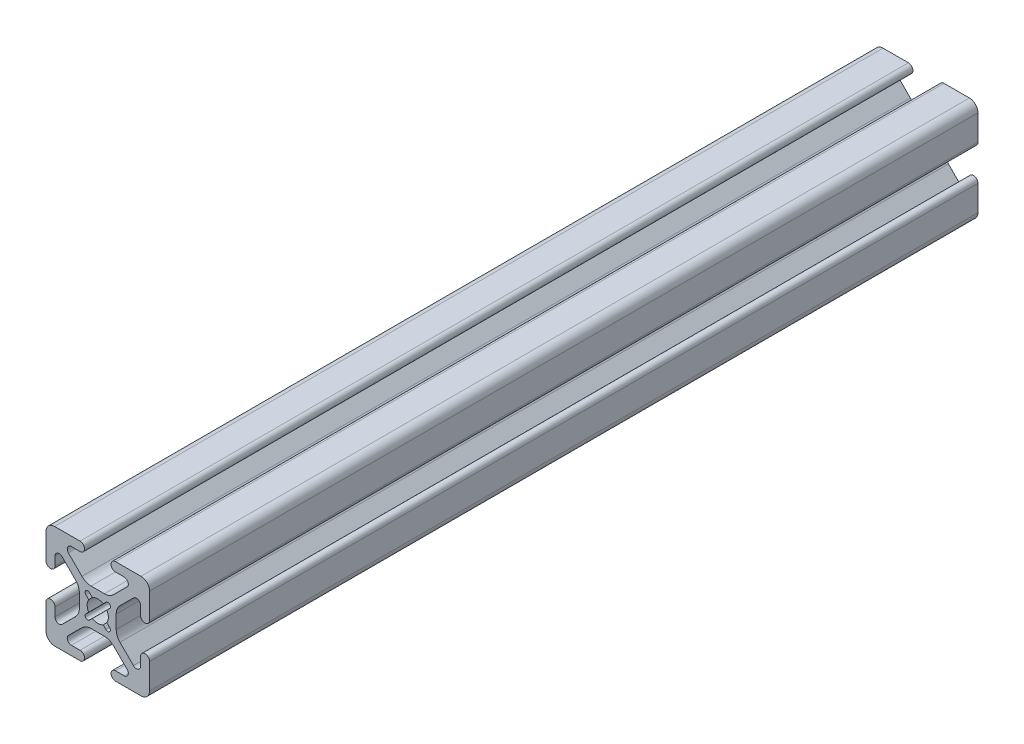
SolidWorks part; units mm, degrees
material "6105-T5 Aluminum"
ref_plane "Front Plane" through (0, 0, 0) normal (0, 0, 1) x (1, 0, 0)
ref_plane "Top Plane" through (0, 0, 0) normal (0, 1, 0) x (1, 0, 0)
ref_plane "Right Plane" through (0, 0, 0) normal (1, 0, 0) x (0, 0, -1)
sketch "Sketch1" plane through (0, 0, 0) normal (0, 0, 1) x (1, 0, 0)
  line L0 (-2.8605, -1.9692) -> (-2.2319, -1.3405)
  line L1 (-2.2319, 1.3405) -> (-2.8605, 1.9692)
  line L2 (-1.9692, 2.8605) -> (-1.3405, 2.2319)
  line L3 (1.3405, 2.2319) -> (1.9692, 2.8605)
  line L4 (2.8605, 1.9692) -> (2.2319, 1.3405)
  line L5 (2.2319, -1.3405) -> (2.8605, -1.9692)
  line L6 (1.9692, -2.8605) -> (1.3405, -2.2319)
  line L7 (-1.3405, -2.2319) -> (-1.9692, -2.8605)
  line L8 (-3.8846, 5.4471) -> (-7.1933, 8.7558)
  line L9 (1.6396, 4.5172) -> (-1.6396, 4.5172)
  line L10 (7.1933, 8.7558) -> (3.8846, 5.4471)
  line L11 (12.7, -10.5918) -> (12.7, -4.3561)
  line L12 (5.4471, 3.8846) -> (8.7558, 7.1933)
  line L13 (4.5172, -1.6396) -> (4.5172, 1.6396)
  line L14 (8.7558, -7.1933) -> (5.4471, -3.8846)
  line L15 (-10.5918, -12.7) -> (-4.3561, -12.7)
  line L16 (3.8846, -5.4471) -> (7.1933, -8.7558)
  line L17 (-1.6396, -4.5172) -> (1.6396, -4.5172)
  line L18 (-7.1933, -8.7558) -> (-3.8846, -5.4471)
  line L19 (-12.7, 10.5918) -> (-12.7, 4.3561)
  line L20 (-5.4471, -3.8846) -> (-8.7558, -7.1933)
  line L21 (-4.5172, 1.6396) -> (-4.5172, -1.6396)
  line L22 (-8.7558, 7.1933) -> (-5.4471, 3.8846)
  line L23 (-10.5918, 12.7) -> (-4.3561, 12.7)
  line L24 (-6.4749, 10.4902) -> (-4.3561, 10.4902)
  line L25 (-10.4902, 6.4749) -> (-10.4902, 4.3561)
  line L26 (-6.4749, -10.4902) -> (-4.3561, -10.4902)
  line L27 (10.4902, -6.4749) -> (10.4902, -4.3561)
  line L28 (4.3561, 12.7) -> (10.5918, 12.7)
  line L29 (4.3561, 10.4902) -> (6.4749, 10.4902)
  line L30 (-10.4902, -4.3561) -> (-10.4902, -6.4749)
  line L31 (-12.7, -4.3561) -> (-12.7, -10.5918)
  line L32 (4.3561, -10.4902) -> (6.4749, -10.4902)
  line L33 (4.3561, -12.7) -> (10.5918, -12.7)
  line L34 (12.7, 4.3561) -> (12.7, 10.5918)
  line L35 (10.4902, 4.3561) -> (10.4902, 6.4749)
  arc A0 (-2.8605, -1.9692) -> (-1.9692, -2.8605) centre (-2.4696, -2.4696) ccw
  arc A1 (-2.2319, 1.3405) -> (-2.2319, -1.3405) centre (0, 0) ccw
  arc A2 (-1.9692, 2.8605) -> (-2.8605, 1.9692) centre (-2.4696, 2.4696) ccw
  arc A3 (1.3405, 2.2319) -> (-1.3405, 2.2319) centre (0, 0) ccw
  arc A4 (2.8605, 1.9692) -> (1.9692, 2.8605) centre (2.4696, 2.4696) ccw
  arc A5 (2.2319, -1.3405) -> (2.2319, 1.3405) centre (0, 0) ccw
  arc A6 (1.9692, -2.8605) -> (2.8605, -1.9692) centre (2.4696, -2.4696) ccw
  arc A7 (-1.3405, -2.2319) -> (1.3405, -2.2319) centre (0, 0) ccw
  arc A8 (-3.8846, 5.4471) -> (-1.6396, 4.5172) centre (-1.6396, 7.6922) ccw
  arc A9 (1.6396, 4.5172) -> (3.8846, 5.4471) centre (1.6396, 7.6922) ccw
  arc A10 (5.4471, 3.8846) -> (4.5172, 1.6396) centre (7.6922, 1.6396) ccw
  arc A11 (4.5172, -1.6396) -> (5.4471, -3.8846) centre (7.6922, -1.6396) ccw
  arc A12 (3.8846, -5.4471) -> (1.6396, -4.5172) centre (1.6396, -7.6922) ccw
  arc A13 (-1.6396, -4.5172) -> (-3.8846, -5.4471) centre (-1.6396, -7.6922) ccw
  arc A14 (-5.4471, -3.8846) -> (-4.5172, -1.6396) centre (-7.6922, -1.6396) ccw
  arc A15 (-4.5172, 1.6396) -> (-5.4471, 3.8846) centre (-7.6922, 1.6396) ccw
  arc A16 (-12.7, -10.5918) -> (-10.5918, -12.7) centre (-10.5918, -10.5918) ccw
  arc A17 (10.5918, -12.7) -> (12.7, -10.5918) centre (10.5918, -10.5918) ccw
  arc A18 (12.7, 10.5918) -> (10.5918, 12.7) centre (10.5918, 10.5918) ccw
  arc A19 (-10.5918, 12.7) -> (-12.7, 10.5918) centre (-10.5918, 10.5918) ccw
  arc A20 (-8.7558, 7.1933) -> (-10.4902, 6.4749) centre (-9.4742, 6.4749) ccw
  arc A21 (-6.4749, 10.4902) -> (-7.1933, 8.7558) centre (-6.4749, 9.4742) ccw
  arc A22 (7.1933, 8.7558) -> (6.4749, 10.4902) centre (6.4749, 9.4742) ccw
  arc A23 (10.4902, 6.4749) -> (8.7558, 7.1933) centre (9.4742, 6.4749) ccw
  arc A24 (8.7558, -7.1933) -> (10.4902, -6.4749) centre (9.4742, -6.4749) ccw
  arc A25 (6.4749, -10.4902) -> (7.1933, -8.7558) centre (6.4749, -9.4742) ccw
  arc A26 (-7.1933, -8.7558) -> (-6.4749, -10.4902) centre (-6.4749, -9.4742) ccw
  arc A27 (-10.4902, -6.4749) -> (-8.7558, -7.1933) centre (-9.4742, -6.4749) ccw
  arc A28 (-4.3561, 10.4902) -> (-4.3561, 12.7) centre (-4.3561, 11.5951) ccw
  arc A29 (4.3561, 12.7) -> (4.3561, 10.4902) centre (4.3561, 11.5951) ccw
  arc A30 (-12.7, 4.3561) -> (-10.4902, 4.3561) centre (-11.5951, 4.3561) ccw
  arc A31 (-10.4902, -4.3561) -> (-12.7, -4.3561) centre (-11.5951, -4.3561) ccw
  arc A32 (-4.3561, -12.7) -> (-4.3561, -10.4902) centre (-4.3561, -11.5951) ccw
  arc A33 (4.3561, -10.4902) -> (4.3561, -12.7) centre (4.3561, -11.5951) ccw
  arc A34 (12.7, -4.3561) -> (10.4902, -4.3561) centre (11.5951, -4.3561) ccw
  arc A35 (10.4902, 4.3561) -> (12.7, 4.3561) centre (11.5951, 4.3561) ccw
extrude "Extrude1" add sketch "Sketch1" against normal blind 203.2
